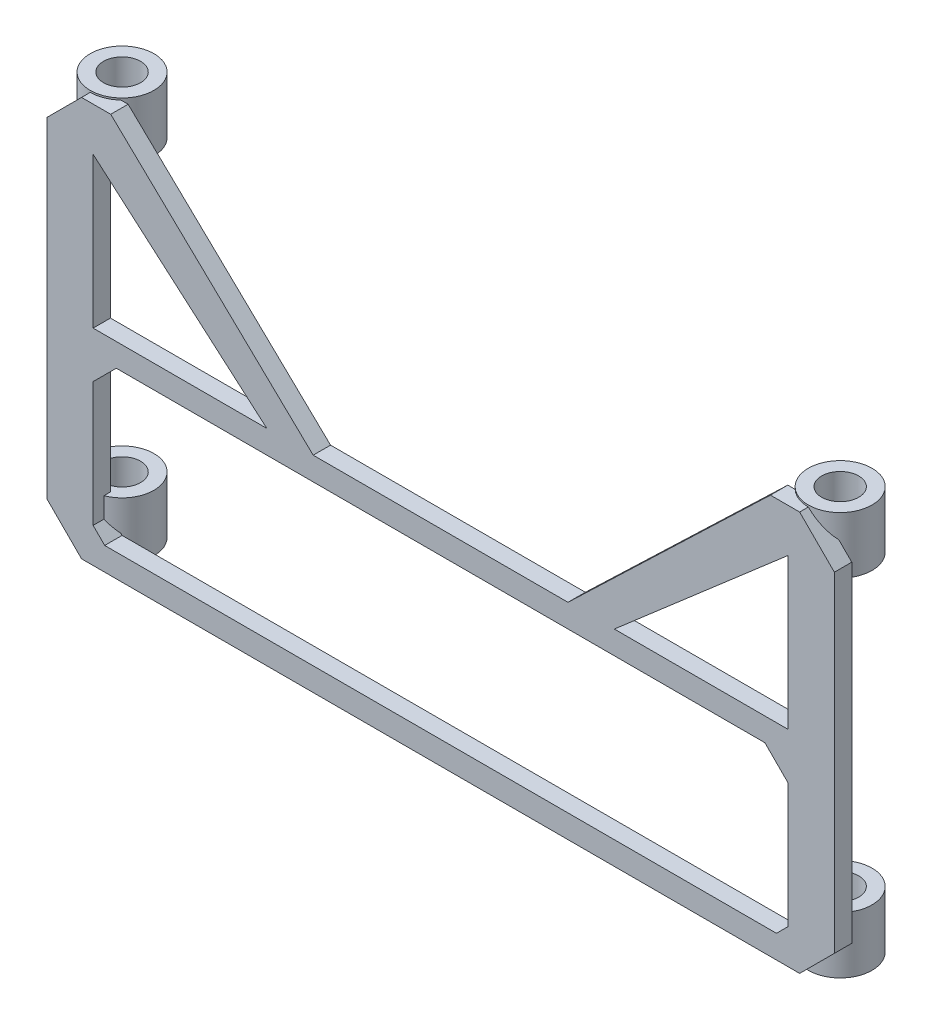
SolidWorks part; units mm, degrees
material "灰色PLA_FDM_原料密度暂定1240"
ref_plane "前视基准面" through (0, 0, 0) normal (0, 0, 1) x (1, 0, 0)
ref_plane "上视基准面" through (0, 0, 0) normal (0, 1, 0) x (1, 0, 0)
ref_plane "右视基准面" through (0, 0, 0) normal (1, 0, 0) x (0, 0, -1)
other "Configuration Table"
sketch "草图1" plane through (0, 0, 0) normal (0, 0, 1) x (1, 0, 0)
  line L0 (-62, 7.5) -> (62, 7.5)
  line L1 (62, 7.5) -> (68, 13.5)
  line L2 (68, 13.5) -> (68, 70.5)
  line L3 (68, 70.5) -> (62, 76.5)
  line L4 (62, 76.5) -> (-62, 76.5)
  line L5 (-62, 76.5) -> (-68, 70.5)
  line L6 (-68, 70.5) -> (-68, 13.5)
  line L7 (-68, 13.5) -> (-62, 7.5)
extrude "斜切侧罩_3mm外壳" add sketch "草图1" along normal blind 3
sketch "草图2" plane through (0, 0, 0) normal (0, 0, 1) x (1, 0, 0)
  line L0 (-58, 11.5) -> (58, 11.5)
  line L1 (58, 11.5) -> (60, 13.5)
  line L2 (60, 13.5) -> (60, 35)
  line L3 (60, 35) -> (56, 39)
  line L4 (56, 39) -> (-56, 39)
  line L5 (-56, 39) -> (-60, 35)
  line L6 (-60, 35) -> (-60, 13.5)
  line L7 (-60, 13.5) -> (-58, 11.5)
  line L8 (-22, 43) -> (22, 43)
  line L9 (22, 43) -> (58, 77.5)
  line L10 (58, 77.5) -> (-58, 77.5)
  line L11 (-58, 77.5) -> (-22, 43)
  line L12 (-30, 43) -> (-60, 43)
  line L13 (-60, 43) -> (-60, 69)
  line L14 (-60, 69) -> (-30, 43)
  line L15 (30, 43) -> (60, 43)
  line L16 (60, 43) -> (60, 69)
  line L17 (60, 69) -> (30, 43)
extrude "接口大窗及斜切散热镂空_开顶避索" cut sketch "草图2" along normal blind 3
sketch "草图3" plane through (0, 0, 0) normal (0, 1, 0) x (1, 0, 0)
  circle A0 centre (-62, 4) radius 5.5
  circle A1 centre (-62, 4) radius 3.2
extrude "免螺丝套柱_D6p4_-1_7.2" add sketch "草图3" along normal blind 9.8 from offset 7.2
sketch "草图4" plane through (0, 0, 0) normal (0, 1, 0) x (1, 0, 0)
  circle A0 centre (-62, 4) radius 5.5
  circle A1 centre (-62, 4) radius 3.2
extrude "免螺丝套柱_D6p4_-1_67" add sketch "草图4" along normal blind 9.8 from offset 67
sketch "草图5" plane through (0, 0, 0) normal (0, 1, 0) x (1, 0, 0)
  circle A0 centre (62, 4) radius 5.5
  circle A1 centre (62, 4) radius 3.2
extrude "免螺丝套柱_D6p4_1_7.2" add sketch "草图5" along normal blind 9.8 from offset 7.2
sketch "草图6" plane through (0, 0, 0) normal (0, 1, 0) x (1, 0, 0)
  circle A0 centre (62, 4) radius 5.5
  circle A1 centre (62, 4) radius 3.2
extrude "免螺丝套柱_D6p4_1_67" add sketch "草图6" along normal blind 9.8 from offset 67
